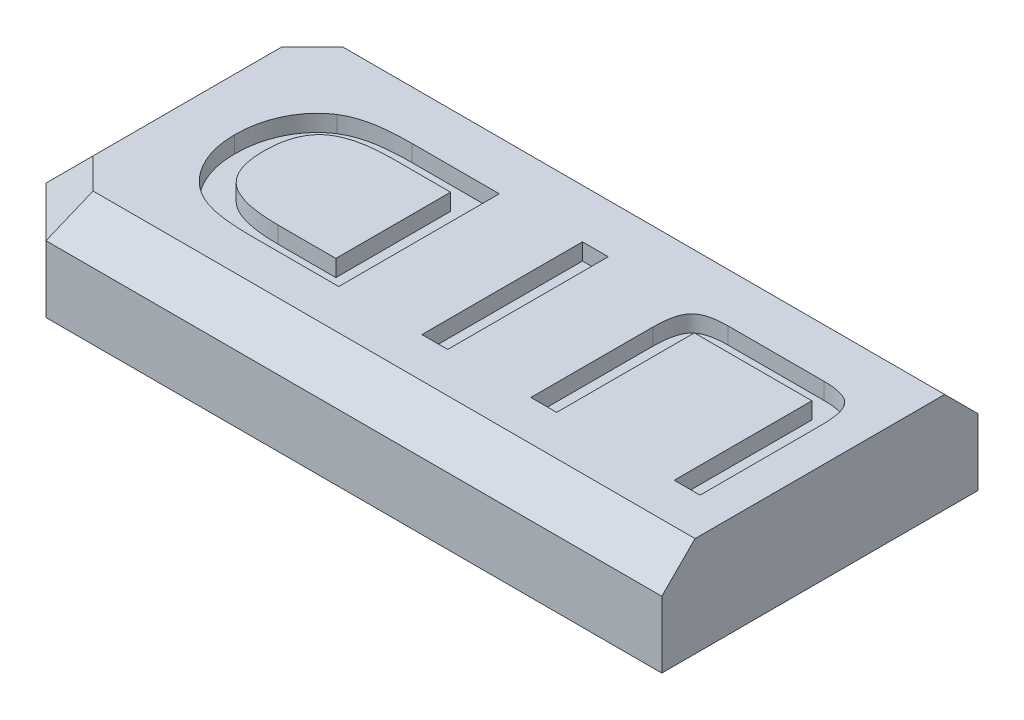
SolidWorks part; units mm, degrees
ref_plane "Front Plane" through (0, 0, 0) normal (0, 0, 1) x (1, 0, 0)
ref_plane "Top Plane" through (0, 0, 0) normal (0, 1, 0) x (1, 0, 0)
ref_plane "Right Plane" through (0, 0, 0) normal (1, 0, 0) x (0, 0, -1)
sketch "Sketch1" plane through (0, -196.7989, 0) normal (0, 1, 0) x (1, 0, 0)
  line L0 (-111.7262, -390.6201) -> (-307.2262, -390.6201) construction
  line L1 (-110.6955, -390.6201) -> (-70.6955, -390.6201)
  line L3 (-110.6955, -409.6201) -> (-70.6955, -409.6201)
  line L4 (-70.6955, -390.6201) -> (-70.6955, -409.6201)
  line L5 (-110.6955, -409.6201) -> (-151.6955, -409.6201)
  line L7 (-110.6955, -390.6201) -> (-151.6955, -390.6201)
  line L8 (-151.6955, -409.6201) -> (-151.6955, -390.6201)
  dimension "D1" = 40
  dimension "D2" = 19
  dimension "D3" = 41
extrude "Boss-Extrude1" add sketch "Sketch1" along normal blind 6
sketch "Sketch2" plane through (0, -190.7989, 0) normal (0, 1, 0) x (1, 0, 0)
  line L0 (-148.0955, -395.5609) -> (-72.8625, -395.5609) construction
  line L3 (-70.6955, -390.6201) -> (-151.6955, -390.6201) construction
  line L4 (-151.6955, -390.6201) -> (-151.6955, -409.6201) construction
  text T0 "LIQUID" font "BankGothic Lt BT" height in points 36
  dimension "D1" = 360
  dimension "D2" = 3.6
extrude "Cut-Extrude1" cut sketch "Sketch2" against normal blind 1
sketch "Sketch3" plane through (0, -190.7989, 0) normal (0, 1, 0) x (1, 0, 0)
  line L0 (-111.1955, -390.6201) -> (-111.1955, -409.6201) construction
  line L1 (-70.6955, -390.6201) -> (-151.6955, -390.6201) construction
  line L2 (-151.6955, -409.6201) -> (-70.6955, -409.6201) construction
  line L4 (-111.6955, -384.1358) -> (-61.8814, -384.1358)
  line L5 (-111.6955, -384.1358) -> (-111.6955, -418.8354)
  line L6 (-111.6955, -418.8354) -> (-61.8814, -418.8354)
  line L7 (-61.8814, -384.1358) -> (-61.8814, -418.8354)
  dimension "D1" = 0.5
extrude "Cut-Extrude2" cut sketch "Sketch3" against normal blind 10
chamfer "Chamfer1" distance 3 angle 45 2 edges at (-151.6955, -193.7989, 409.6201) (-151.6955, -193.7989, 390.6201)
chamfer "Chamfer2" distance 2 angle 45 5 edges at (-130.1955, -190.7989, 390.6201) (-150.1955, -190.7989, 392.1201) (-151.6955, -190.7989, 400.1201) (-150.1955, -190.7989, 408.1201) (-130.1955, -190.7989, 409.6201)
sketch "Sketch4" plane through (0, -196.7989, 0) normal (0, -1, 0) x (1, 0, 0)
  line L0 (-111.6955, 409.6201) -> (-111.6955, 390.6201) construction
  line L1 (-148.6955, 409.6201) -> (-111.6955, 409.6201) construction
  circle A0 centre (-131.1955, 400.1201) radius 4.1
  dimension "D1" = 8.2
  dimension "D2" = 19.5
  dimension "D3" = 9.5
extrude "Cut-Extrude3" cut sketch "Sketch4" against normal blind 3.4
